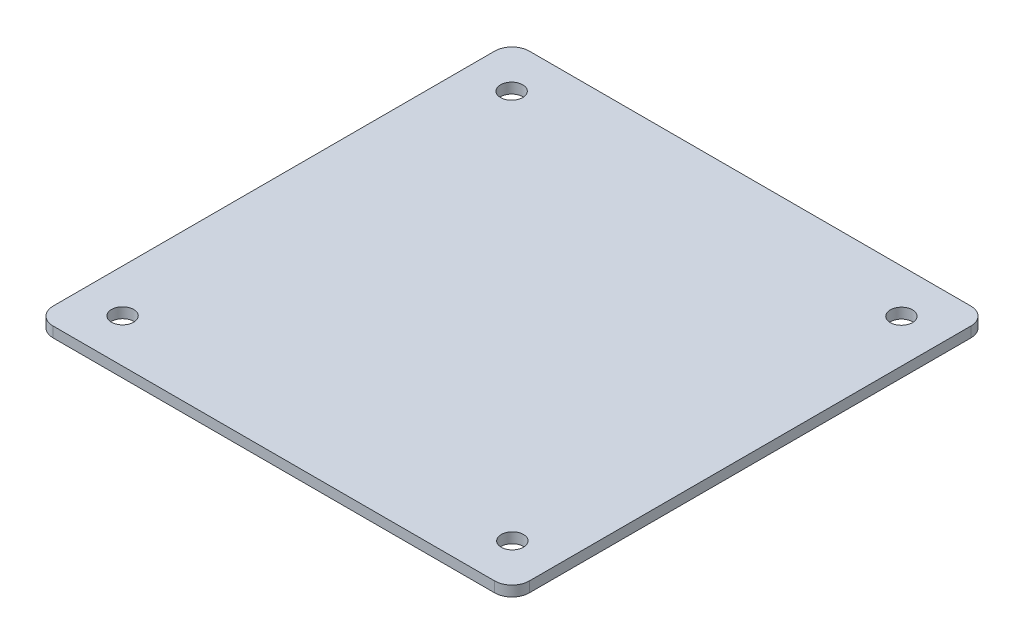
SolidWorks part; units mm, degrees
ref_plane "Front Plane" through (0, 0, 0) normal (0, 0, 1) x (1, 0, 0)
ref_plane "Top Plane" through (0, 0, 0) normal (0, 1, 0) x (1, 0, 0)
ref_plane "Right Plane" through (0, 0, 0) normal (1, 0, 0) x (0, 0, -1)
sketch "Sketch1" plane through (0, 0, 0) normal (0, 1, 0) x (1, 0, 0)
  line L0 (35.5, 55.5) -> (35.5, -14.5) construction
  line L1 (0.5, -14.5) -> (70.5, -14.5)
  line L2 (0.5, -14.5) -> (0.5, 55.5)
  line L3 (0.5, 55.5) -> (70.5, 55.5)
  line L4 (70.5, -14.5) -> (70.5, 55.5)
  line L5 (0.5, 20.5) -> (70.5, 20.5) construction
  circle A0 centre (6.85, 49.0981) radius 1.6319
  circle A1 centre (6.85, -8.0981) radius 1.6319
  circle A2 centre (64.15, -8.0981) radius 1.6319
  circle A3 centre (64.15, 49.0981) radius 1.6319
  dimension "D3" = 3.2639
  dimension "D1" = 70
  dimension "D2" = 70
  dimension "D4" = 6.4019
  dimension "D5" = 6.35
extrude "Boss-Extrude1" add sketch "Sketch1" along normal blind 1.524
fillet "Fillet1" radius 2.54 4 edges at (70.5, 0.762, 14.5) (70.5, 0.762, -55.5) (0.5, 0.762, -55.5) (0.5, 0.762, 14.5)
